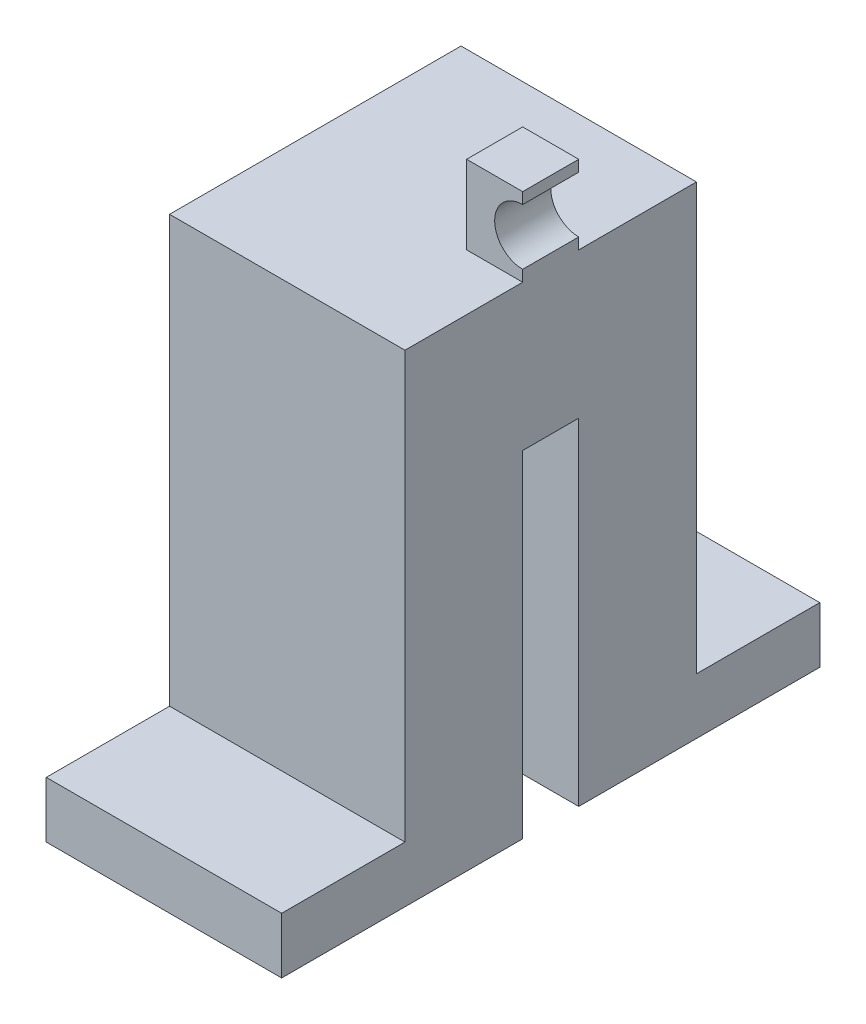
SolidWorks part; units mm, degrees
ref_plane "前视基准面" through (0, 0, 0) normal (0, 0, 1) x (1, 0, 0)
ref_plane "上视基准面" through (0, 0, 0) normal (0, 1, 0) x (1, 0, 0)
ref_plane "右视基准面" through (0, 0, 0) normal (1, 0, 0) x (0, 0, -1)
sketch "草图1" plane through (0, 0, 0) normal (0, 1, 0) x (1, 0, 0)
  line L2 (0, -8.5) -> (0, -1)
  line L3 (0, 8.5) -> (21, 8.5)
  line L9 (0, -8.5) -> (21, -8.5)
  line L17 (0, -1) -> (-2, -1)
  line L18 (-2, -1) -> (-2, -3)
  line L19 (-2, -3) -> (-4, -3)
  line L20 (-4, -3) -> (-4, 3)
  line L21 (0, 1) -> (-2, 1)
  line L22 (-2, 1) -> (-2, 3)
  line L23 (-2, 3) -> (-4, 3)
  line L25 (21, 8.5) -> (21, -8.5)
  line L26 (0, 1) -> (0, 8.5)
  point P11 (7, 0)
  point P15 (14, 0)
  point P18 (0, 0)
  point P32 (-4, 0)
  dimension "D1" = 21
  dimension "D8" = 2
  dimension "D9" = 2
  dimension "D10" = 2
  dimension "D11" = 3
  dimension "D12" = 1
extrude "凸台-拉伸1" add sketch "草图1" along normal blind 50 contours L26 L3 L25 L9 L2 L17 L18 L19 L20 L23 L22 L21
sketch "草图3" plane through (0, 0, 0) normal (0, -1, 0) x (1, 0, 0)
  line L0 (-4, 0.1032) -> (-4, 0) construction
  line L1 (-4, 3) -> (-4, -3) construction
  line L2 (-4, 0) -> (26.0372, 0) construction
  line L3 (3, -3.5) -> (11, -3.5)
  line L4 (3, -3.5) -> (3, 3.5)
  line L5 (3, 3.5) -> (11, 3.5)
  line L6 (11, 3.5) -> (11, -3.5)
  line L7 (0, 8.5) -> (0, 1) construction
  line L8 (0, 8.5) -> (21, 8.5) construction
  point P11 (11, 0)
  point P12 (3, 0)
extrude "切除-拉伸1" cut sketch "草图3" against normal blind 31.3896
sketch "草图6" plane through (0, 0, 0) normal (0, -1, 0) x (1, 0, 0)
  line L0 (21, 0) -> (21, 2.5)
  line L1 (21, -8.5) -> (21, 8.5) construction
  line L2 (21, 2.5) -> (14, 2.5)
  line L3 (14, 2.5) -> (14, -2.5)
  line L4 (21, -2.5) -> (14, -2.5)
  line L5 (21.0941, -2.5) -> (21, -2.4059)
  line L6 (21, -2.4059) -> (21, 0)
  point P9 (21, 1.25)
extrude "切除-拉伸2" cut sketch "草图6" against normal blind 30 and the other way through all
sketch "草图15" plane through (21, 0, 0) normal (1, 0, 0) x (0, 0, -1)
  line L0 (0, 0) -> (0, 50) construction
  line L1 (8.5, 50) -> (-8.5, 50) construction
  line L2 (-8.5, 50) -> (-2.5, 50)
  line L3 (2.5, 50) -> (2.5, 43)
  line L4 (2.5, 43) -> (8.5, 43)
  line L5 (8.5, 50) -> (8.5, 0) construction
  line L6 (8.5, 43) -> (8.5, 50)
  line L7 (8.5, 50) -> (2.5, 50)
  line L8 (-8.5, 43) -> (-8.5, 50)
  line L9 (-2.5, 43) -> (-8.5, 43)
  line L10 (-2.5, 50) -> (-2.5, 43)
extrude "切除-拉伸10" cut sketch "草图15" against normal blind 30
sketch "草图16" plane through (0, 0, 2.5) normal (0, 0, 1) x (1, 0, 0)
  line L0 (21, 50) -> (16, 50)
  line L1 (0, 50) -> (21, 50) construction
  line L2 (16, 50) -> (16, 43)
  line L3 (0, 43) -> (21, 43) construction
  line L4 (16, 43) -> (-6.9217, 43)
  line L5 (-6.9217, 43) -> (-6.9217, 50)
  line L6 (-6.9217, 50) -> (16, 50)
  line M5 (0, 50) -> (0, 43)
  line M6 (0, 43) -> (21, 43)
  line M8 (21, 50) -> (0, 50)
extrude "切除-拉伸11" cut sketch "草图16" against normal blind 30 contours L2 M8 M5 M6 | L6 L5 L4 M5
sketch "草图18" plane through (0, 0, -2.5) normal (0, 0, -1) x (-1, 0, 0)
  line L0 (-21, 43) -> (-21, 50) construction
  circle A0 centre (-21, 46.5) radius 2.5
extrude "切除-拉伸12" cut sketch "草图18" against normal blind 30
sketch "草图19" plane through (0, 0, 0) normal (0, -1, 0) x (-1, 0, 0)
  line L0 (-21, -8.5) -> (-21, -5.5)
  line L1 (-21, -2.5) -> (-21, -8.5) construction
  line L2 (-21, -5.5) -> (0, -5.5)
  line L3 (0, -8.5) -> (0, -1) construction
  line L4 (0, -5.5) -> (0, -8.5)
  line L5 (0, -8.5) -> (-21, -8.5)
  line L6 (4, 0) -> (-21, 0) construction
  line L7 (4, -3) -> (4, 3) construction
  line L8 (-21, 2.5) -> (-21, -2.5) construction
  line L9 (0, 5.5) -> (0, 8.5)
  line L10 (-21, 5.5) -> (0, 5.5)
  line L11 (-21, 8.5) -> (-21, 5.5)
  line L12 (0, 8.5) -> (-21, 8.5)
extrude "切除-拉伸14" cut sketch "草图19" against normal blind 50 contours L5 L0 L2 L4 | L9 L12 L11 L10
sketch "草图20" plane through (0, 0, 0) normal (0, -1, 0) x (1, 0, 0)
  line L0 (0, -1) -> (0, -5.5) construction
  line L1 (-4, 3) -> (0, 3)
  line L2 (-4, 3) -> (-4, -3.0196)
  line L3 (-4, -3.0196) -> (0, -3.0196)
  line L4 (0, 3) -> (0, -3.0196)
  line L5 (-2, -3.0196) -> (-2, 3) construction
  line L6 (-4, -0.0098) -> (0, -0.0098) construction
  point P169 (-2, -0.0098)
extrude "切除-拉伸16" cut sketch "草图20" against normal blind 50
sketch "草图21" plane through (0, 0, 0) normal (0, -1, 0) x (1, 0, 0)
  line L0 (0, -5.5) -> (0, -13)
  line L1 (0, -13) -> (21, -13)
  line L2 (21, -13) -> (21, -5.5)
  line L3 (21, -5.5) -> (0, -5.5)
  line L4 (0, 0) -> (21, 0) construction
  line L7 (0, 5.5) -> (0, -5.5) construction
  line L8 (21, -2.5) -> (21, 2.5) construction
  line L9 (21, 13) -> (21, 5.5)
  line L10 (0, 13) -> (21, 13)
  line L11 (0, 5.5) -> (0, 13)
  line L12 (21, 5.5) -> (0, 5.5)
  point P10 (0, 0)
extrude "凸台-拉伸3" add sketch "草图21" against normal up to vertex
sketch "草图22" plane through (0, 0, 13) normal (0, 0, 1) x (1, 0, 0)
  line L1 (21, 0) -> (21, 5)
  line L2 (21, 43) -> (21, 0) construction
  line L3 (21, 5) -> (0, 5)
  line L4 (0, 43) -> (0, 0) construction
  line L5 (0, 5) -> (0, 0)
  line L6 (0, 0) -> (21, 0)
extrude "凸台-拉伸4" add sketch "草图22" along normal blind 11
sketch "草图23" plane through (0, 0, -13) normal (0, 0, -1) x (-1, 0, 0)
  line L0 (0, 0) -> (0, 5)
  line L1 (0, 43) -> (0, 0) construction
  line L2 (0, 5) -> (-21, 5)
  line L3 (-21, 5) -> (-21, 0)
  line L4 (-21, 0) -> (0, 0)
extrude "凸台-拉伸5" add sketch "草图23" along normal blind 11
